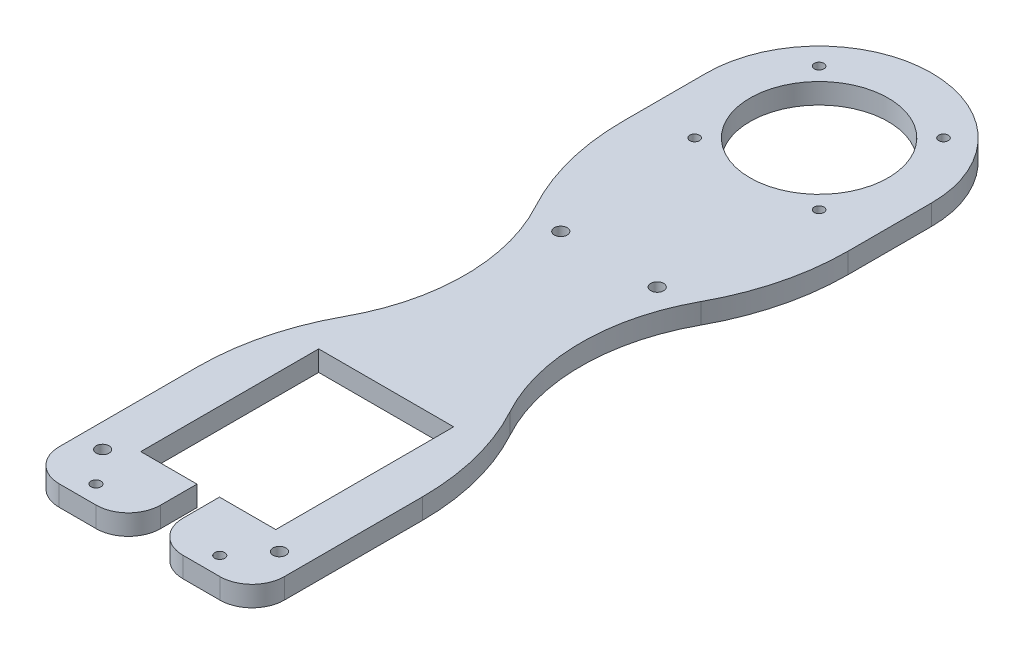
SolidWorks part; units mm, degrees
ref_plane "Front Plane" through (0, 0, 0) normal (0, 0, 1) x (1, 0, 0)
ref_plane "Top Plane" through (0, 0, 0) normal (0, 1, 0) x (1, 0, 0)
ref_plane "Right Plane" through (0, 0, 0) normal (1, 0, 0) x (0, 0, -1)
sketch "Sketch1" plane through (0, 0, 0) normal (0, 1, 0) x (1, 0, 0)
  line L0 (-35, 0) -> (-35, -211.35)
  line L1 (-35, -211.35) -> (35, -211.35)
  line L2 (35, -211.35) -> (35, 0)
  circle A0 centre (0, 0) radius 35
  point P3 (0, -211.35)
  dimension "D1" = 70
  dimension "D2" = 70
  dimension "D3" = 211.35
extrude "Boss-Extrude1" add sketch "Sketch1" along normal mid plane 6.35
sketch "Sketch2" plane through (0, 3.175, 0) normal (0, 1, 0) x (1, 0, 0)
  circle A0 centre (0, 0) radius 21.5
  dimension "D1" = 43
extrude "Cut-Extrude1" cut sketch "Sketch2" against normal through all
sketch "Sketch3" plane through (0, 3.175, 0) normal (0, 1, 0) x (1, 0, 0)
  line L1 (21, -190) -> (-21, -190)
  line L2 (21, -190) -> (21, -134.65)
  line L3 (21, -134.65) -> (-21, -134.65)
  line L4 (-21, -190) -> (-21, -134.65)
  line L5 (21, -190) -> (-21, -134.65) construction
  line L6 (21, -134.65) -> (-21, -190) construction
  line L11 (-35, -211.35) -> (35, -211.35) construction
  line L13 (3.5, -211.35) -> (-3.5, -211.35)
  line L14 (3.5, -211.35) -> (3.5, -190)
  line L15 (3.5, -190) -> (-3.5, -190)
  line L16 (-3.5, -211.35) -> (-3.5, -190)
  line L17 (3.5, -211.35) -> (-3.5, -190) construction
  line L18 (3.5, -190) -> (-3.5, -211.35) construction
  point P0 (0, -162.325)
  point P8 (0, -200.675)
  line M13 (-35, -211.35) -> (35, -211.35)
  dimension "D1" = 21.35
  dimension "D2" = 42
  dimension "D3" = 7
  dimension "48" = 55.35
extrude "Cut-Extrude2" cut sketch "Sketch3" against normal through all contours L4 L1 L2 L3 | L16 L14 L1 M13
sketch "Sketch4" plane through (0, 3.175, 0) normal (0, 1, 0) x (1, 0, 0)
  line L0 (-19.35, 19.35) -> (-19.35, -19.35) construction
  line L1 (-19.35, -19.35) -> (19.35, -19.35) construction
  line L2 (19.35, -19.35) -> (19.35, 19.35) construction
  line L3 (19.35, 19.35) -> (-19.35, 19.35) construction
  circle A0 centre (-19.35, 19.35) radius 1.5
  circle A1 centre (19.35, 19.35) radius 1.5
  circle A2 centre (19.35, -19.35) radius 1.5
  circle A3 centre (-19.35, -19.35) radius 1.5
  point P8 (19.35, 0)
  point P9 (0, 19.35)
  dimension "D2" = 3
  dimension "D1" = 38.7
extrude "Cut-Extrude3" cut sketch "Sketch4" against normal through all
fillet "Fillet1" radius 10 4 edges at (-3.5, 0, 211.35) (3.5, 0, 211.35) (-35, 0, 211.35) (35, 0, 211.35)
sketch "Sketch5" plane through (0, 3.175, 0) normal (0, 1, 0) x (1, 0, 0)
  line L0 (-15, -65.35) -> (15, -65.35) construction
  line L1 (15, -65.35) -> (27.5, -195.35) construction
  line L2 (27.5, -195.35) -> (-27.5, -195.35) construction
  line L3 (-27.5, -195.35) -> (-15, -65.35) construction
  line L4 (-25, -211.35) -> (-13.5, -211.35) construction
  circle A0 centre (-15, -65.35) radius 2
  circle A1 centre (15, -65.35) radius 2
  circle A2 centre (-27.5, -195.35) radius 2
  circle A3 centre (27.5, -195.35) radius 2
  point P8 (0, -65.35)
  point P9 (-28.8537, -199.35)
  point P13 (0, -195.35)
  dimension "D1" = 4
  dimension "D2" = 55
  dimension "D3" = 130
  dimension "D4" = 16
  dimension "D5" = 30
extrude "Cut-Extrude4" cut sketch "Sketch5" against normal through all
sketch "Sketch6" plane through (0, -3.175, 0) normal (0, -1, 0) x (1, 0, 0)
  line L0 (-35, 0) -> (-35, 201.35) construction
  line L1 (-35, 49.65) -> (-35, 134.65)
  arc A0 (-35, 49.65) -> (-35, 134.65) centre (-80, 92.15) ccw
  dimension "D1" = 85
  dimension "D2" = 45
extrude "Cut-Extrude5" cut sketch "Sketch6" against normal through all
mirror "Mirror1" about plane through (0, 0, 0) normal (1, 0, 0) of "Cut-Extrude5"
fillet "Fillet3" radius 76 4 edges at (35, 0, 49.65) (35, 0, 134.65) (-35, 0, 134.65) (-35, 0, 49.65)
sketch "Sketch7" plane through (0, -3.175, 0) normal (0, -1, 0) x (1, 0, 0)
  line L0 (-19.25, 205.675) -> (19.25, 205.675) construction
  line L1 (-25, 211.35) -> (-13.5, 211.35) construction
  circle A0 centre (-19.25, 205.675) radius 1.55
  circle A1 centre (19.25, 205.675) radius 1.55
  point P4 (0, 205.675)
  point P5 (0, 0)
  point P10 (-19.25, 211.35)
  dimension "D1" = 3.1
  dimension "D2" = 5.675
extrude "Cut-Extrude6" cut sketch "Sketch7" against normal through all
